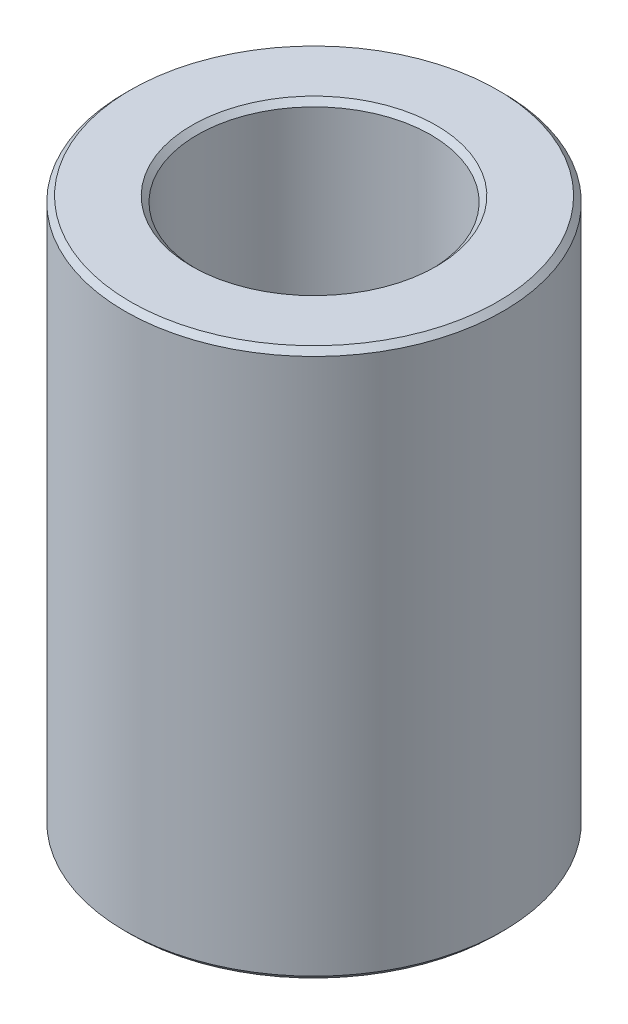
SolidWorks part; units mm, degrees
material "PVC Rigid"
ref_plane "Front Plane" through (0, 0, 0) normal (0, 0, 1) x (1, 0, 0)
ref_plane "Top Plane" through (0, 0, 0) normal (0, 1, 0) x (1, 0, 0)
ref_plane "Right Plane" through (0, 0, 0) normal (1, 0, 0) x (0, 0, -1)
sketch "Sketch2" plane through (0, 0, 0) normal (0, 1, 0) x (1, 0, 0)
  circle A0 centre (0, 0) radius 8.636
  dimension "D1" = 17.272
extrude "Extrude-Thin1" add sketch "Sketch2" along normal mid plane 25.02 thin thin type one direction reverse wall 3.302
chamfer "Chamfer1" distance 0.25 angle 45 4 edges at (5.334, -12.51, 0) (0, -12.51, 8.636) (5.334, 12.51, 0) (0, 12.51, 8.636)
